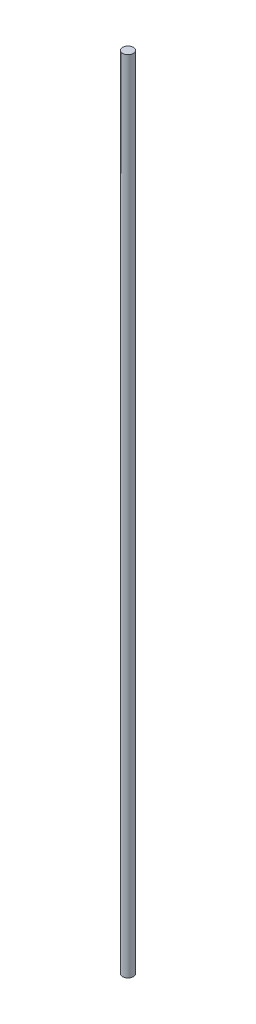
SolidWorks part; units mm, degrees
ref_plane "前视" through (0, 0, 0) normal (0, 0, 1) x (1, 0, 0)
ref_plane "上视" through (0, 0, 0) normal (0, 1, 0) x (1, 0, 0)
ref_plane "右视" through (0, 0, 0) normal (1, 0, 0) x (0, 0, -1)
sketch "Sketch1" plane through (0, 0, 0) normal (0, 1, 0) x (1, 0, 0)
  circle A0 centre (0, 0) radius 4
extrude "Extrude1" add sketch "Sketch1" along normal blind 600
